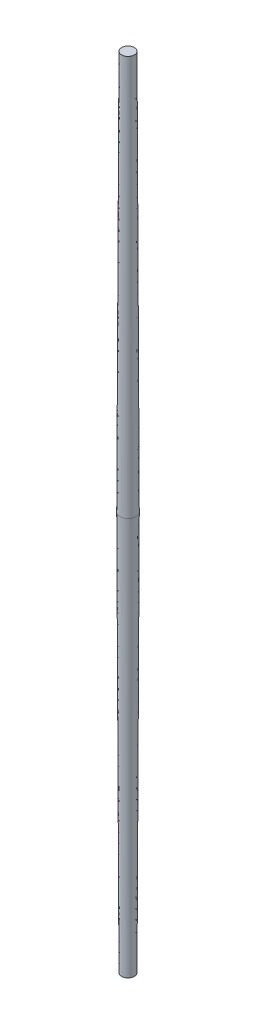
SolidWorks part; units mm, degrees
ref_plane "Plan de face" through (0, 0, 0) normal (0, 0, 1) x (1, 0, 0)
ref_plane "Plan de dessus" through (0, 0, 0) normal (0, 1, 0) x (1, 0, 0)
ref_plane "Plan de droite" through (0, 0, 0) normal (1, 0, 0) x (0, 0, -1)
sketch "Esquisse1" plane through (0, 0, 0) normal (0, 0, 1) x (1, 0, 0)
  line L0 (0, 0) -> (5, 0)
  line L1 (5, 0) -> (4, 250)
  line L2 (4, 250) -> (0, 250)
  line L3 (0, 250) -> (0, 0)
  dimension "D1" = 250
  dimension "D2" = 5
  dimension "D3" = 4
revolve "Révolution1" add sketch "Esquisse1" angle 360 about L3
mirror "Symétrie1" about plane through (0, 0, 0) normal (0, 1, 0) of "Révolution1"
scale "Echelle1" scale about centroid uniform scaling yes scale factor 0.6
